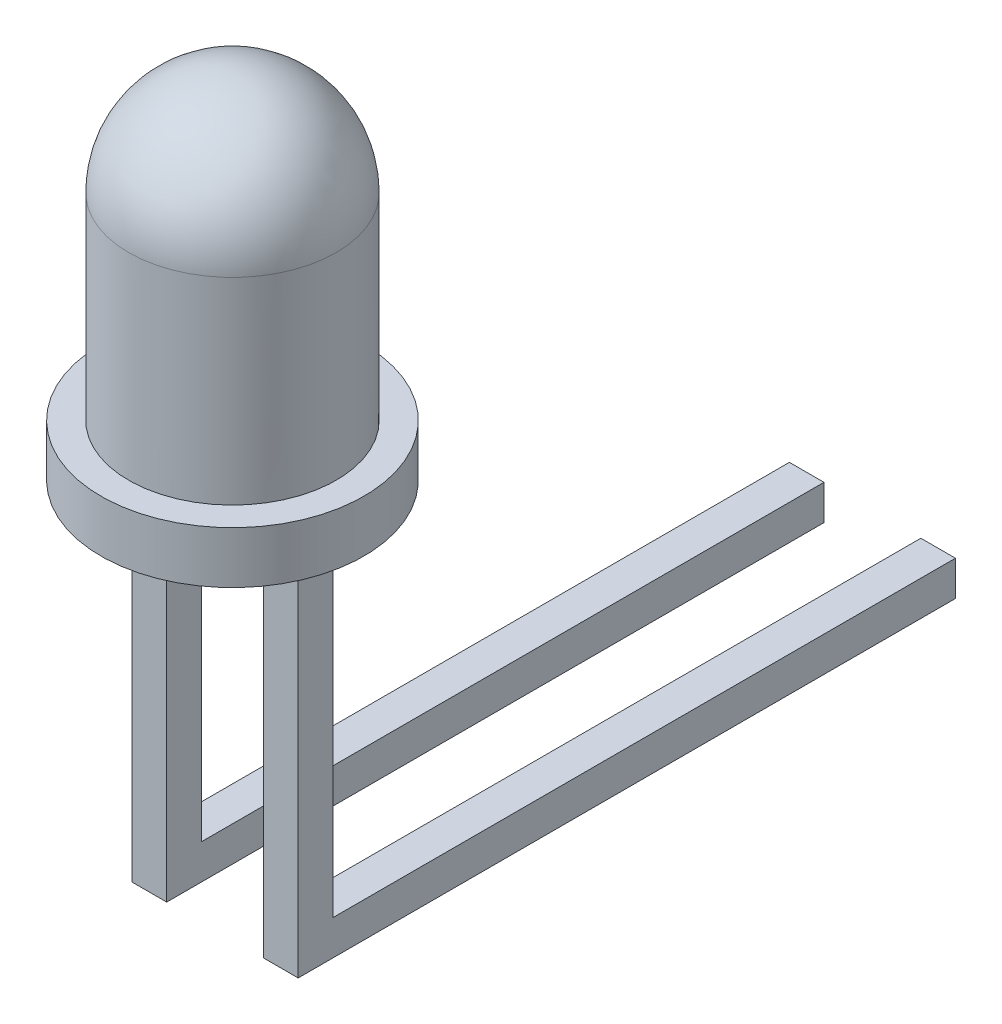
SolidWorks part; units mm, degrees
ref_plane "Přední rovina" through (0, 0, 0) normal (0, 0, 1) x (1, 0, 0)
ref_plane "Horní rovina" through (0, 0, 0) normal (0, 1, 0) x (1, 0, 0)
ref_plane "Pravá rovina" through (0, 0, 0) normal (1, 0, 0) x (0, 0, -1)
sketch "Skica1" plane through (0, 0, 0) normal (0, 0, 1) x (1, 0, 0)
  line L0 (-1.5, 6.0665) -> (-1.5, 3.2165)
  line L1 (-1.9, 2.4665) -> (0, 2.4665)
  line L2 (0, 7.5665) -> (0, 2.4665)
  line L3 (-1.5, 3.2165) -> (-1.9, 3.2165)
  line L4 (-1.9, 3.2165) -> (-1.9, 2.4665)
  line L5 (0, 7.5665) -> (0, 2.4665) construction
  line L6 (0, 7.5665) -> (0, 8.2497) construction
  arc A0 (0, 7.5665) -> (-1.5, 6.0665) centre (0, 6.0665) ccw
  dimension "D1" = 5.1
  dimension "D2" = 3
  dimension "D3" = 3.8
revolve "Rotovat1" add sketch "Skica1" angle 360 about L5
sketch "Skica2" plane through (0, 0, 0) normal (0, 0, 1) x (1, 0, 0)
  line L0 (0.7, 2.4665) -> (1.2, 2.4665)
  line L1 (-1.9, 2.4665) -> (1.9, 2.4665) construction
  line L2 (1.2, 2.4665) -> (1.2, -3.0385)
  line L3 (-0.7, -3.0385) -> (-1.2, -3.0385)
  line L4 (1.2, -3.0385) -> (0.7, -3.0385)
  line L6 (0.7, -3.0385) -> (0.7, 2.4665)
  line L7 (-0.7, 2.4665) -> (-0.7, -3.0385)
  line L11 (-1.2, -3.0385) -> (-1.2, 2.4665)
  line L12 (-0.7, 2.4665) -> (-1.2, 2.4665)
  dimension "D1" = 0.5
  dimension "D2" = 5.505
  dimension "D3" = 0.7
  dimension "D4" = 0.7
  dimension "D5" = 0.5
extrude "Přidat vysunutím1" add sketch "Skica2" along normal mid plane 0.5
sketch "Skica3" plane through (0, 0, -0.25) normal (0, 0, -1) x (-1, 0, 0)
  line L0 (0.7, -3.0385) -> (0.7, 2.4665) construction
  line L1 (1.2, -3.0385) -> (0.7, -3.0385)
  line L2 (1.2, -3.0385) -> (1.2, -2.5337)
  line L3 (1.2, -2.5337) -> (0.7, -2.5337)
  line L4 (0.7, -3.0385) -> (0.7, -2.5337)
  line L5 (-1.2, -3.0385) -> (-1.2, 2.4665) construction
  line L6 (-0.7, -3.0385) -> (-1.2, -3.0385)
  line L7 (-0.7, -3.0385) -> (-0.7, -2.5337)
  line L8 (-0.7, -2.5337) -> (-1.2, -2.5337)
  line L9 (-1.2, -3.0385) -> (-1.2, -2.5337)
  dimension "D1" = 0.5048
  dimension "D2" = 0.5048
extrude "Přidat vysunutím2" add sketch "Skica3" along normal blind 9
